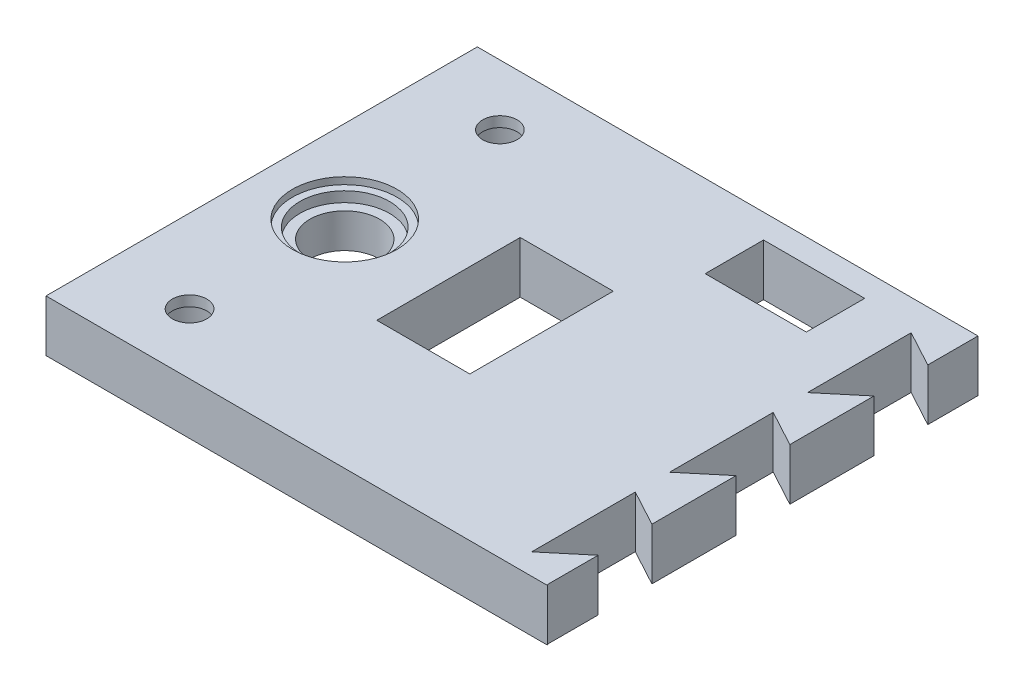
SolidWorks part; units mm, degrees
ref_plane "Front Plane" through (0, 0, 0) normal (0, 0, 1) x (1, 0, 0)
ref_plane "Top Plane" through (0, 0, 0) normal (0, 1, 0) x (1, 0, 0)
ref_plane "Right Plane" through (0, 0, 0) normal (1, 0, 0) x (0, 0, -1)
sketch "Sketch1" plane through (0, 0, 0) normal (0, 1, 0) x (1, 0, 0)
  line L1 (-140, 105) -> (140, 105)
  line L2 (-140, 105) -> (-140, -105)
  line L3 (-140, -105) -> (140, -105)
  line L4 (140, 105) -> (140, -105)
  line L5 (-140, 105) -> (140, -105) construction
  line L6 (-140, -105) -> (140, 105) construction
  point P0 (0, 0)
  dimension "D1" = 280
  dimension "D2" = 210
extrude "Boss-Extrude1" add sketch "Sketch1" along normal blind 15
sketch "Sketch2" plane through (0, 15, 0) normal (0, 1, 0) x (1, 0, 0)
  line L0 (-105, 0) -> (-100, 0) construction
  line L2 (-100, 0) -> (-95, 0) construction
  line L3 (-100, 0) -> (-100, 5) construction
  line L4 (-100, 0) -> (-100, -5) construction
  line L5 (-75, 0) -> (-62.5, 0) construction
  line L6 (-100, -40) -> (-100, -45) construction
  line L7 (-100, 40) -> (-100, 45) construction
  circle A3 centre (-100, 0) radius 5
  circle A4 centre (-100, 45) radius 5
  circle A5 centre (-100, -45) radius 5
  dimension "D3" = 45
  dimension "D4" = 45
  dimension "D2" = 37.5
extrude "Boss-Extrude2" add sketch "Sketch2" along normal blind 50
sketch "Sketch3" plane through (0, 15, 0) normal (0, 1, 0) x (1, 0, 0)
  line L1 (5, 15) -> (-5, 15)
  line L2 (5, 15) -> (5, -15)
  line L3 (5, -15) -> (-5, -15)
  line L4 (-5, 15) -> (-5, -15)
  line L5 (5, 15) -> (-5, -15) construction
  line L6 (5, -15) -> (-5, 15) construction
  point P0 (0, 0)
extrude "Boss-Extrude3" add sketch "Sketch3" along normal up to surface (50 mm away) up to face at (-100, 65, 50)
sketch "Sketch4" plane through (5, 0, 0) normal (1, 0, 0) x (0, 0, -1)
  circle A0 centre (0, 41.2362) radius 13
extrude "Cut-Extrude1" cut sketch "Sketch4" against normal blind 20 contours A0
sketch "Sketch5" plane through (0, 0, 0) normal (0, 1, 0) x (1, 0, 0)
  line L1 (124.0869, 62.5479) -> (-124.0869, 62.5479)
  line L2 (124.0869, 62.5479) -> (124.0869, -62.5479)
  line L3 (124.0869, -62.5479) -> (-124.0869, -62.5479)
  line L4 (-124.0869, 62.5479) -> (-124.0869, -62.5479)
  line L7 (-178.9003, 121.3967) -> (181.5906, 121.3967)
  line L8 (-178.9003, 121.3967) -> (-178.9003, -127.786)
  line L9 (-178.9003, -127.786) -> (181.5906, -127.786)
  line L10 (181.5906, 121.3967) -> (181.5906, -127.786)
  line L11 (-124.0869, 62.5479) -> (124.0869, 62.5479)
  line L13 (-124.0869, 121.3967) -> (181.5906, 121.3967)
  line L14 (181.5906, 62.5479) -> (181.5906, 121.3967)
  line L17 (-124.0869, 121.3967) -> (-178.9003, 121.3967)
  line L18 (-178.9003, 62.5479) -> (-178.9003, 121.3967)
  line L20 (-178.9003, 62.5479) -> (-178.9003, -127.786)
  line L21 (-178.9003, -127.786) -> (-124.0869, -127.786)
  line L22 (-124.0869, 62.5479) -> (-124.0869, -62.5479)
  line L23 (-124.0869, -62.5479) -> (124.0869, -62.5479)
  line L25 (-124.0869, -127.786) -> (181.5906, -127.786)
  line L26 (181.5906, -62.5479) -> (181.5906, -127.786)
  line L28 (124.0869, 62.5479) -> (124.0869, -62.5479)
  line L30 (181.5906, 62.5479) -> (181.5906, -62.5479)
  point P0 (0, 0)
sketch "Sketch6" plane through (0, 0, 0) normal (0, 1, 0) x (1, 0, 0)
extrude "Cut-Extrude5" cut sketch "Sketch5" along normal up to surface (15 mm away) contours L10 L7 L8 L9 L4 L1 L2 L3 up to face at (-100, 15, 50)
sketch "Sketch7" plane through (0, 65, 0) normal (0, 1, 0) x (1, 0, 0)
  circle A0 centre (-100, 45) radius 5
  circle A1 centre (-100, 0) radius 5
  circle A2 centre (-100, -45) radius 5
extrude "Cut-Extrude6" cut sketch "Sketch7" against normal up to surface (65 mm away) up to face at (0, 0, 0)
sketch "Sketch8" plane through (0, 0, 0) normal (0, -1, 0) x (1, 0, 0)
  circle A0 centre (-100, 45) radius 10.1
  circle A1 centre (-100, 0) radius 10.1
  circle A2 centre (-100, -45) radius 10.1
  dimension "D1" = 20.2
  dimension "D2" = 20.2
  dimension "D3" = 20.2
sketch "Sketch9" plane through (0, 15, 0) normal (0, 1, 0) x (1, 0, 0)
  line L0 (-4.7569, 55.5479) -> (-34.0869, 55.5479)
  line L1 (-4.7569, 55.5479) -> (-4.7569, 38.6279)
  line L2 (-4.7569, 38.6279) -> (-34.0869, 38.6279)
  line L3 (-34.0869, 55.5479) -> (-34.0869, 38.6279)
  line L4 (-4.7569, 55.5479) -> (-34.0869, 38.6279) construction
  line L5 (-4.7569, 38.6279) -> (-34.0869, 55.5479) construction
  line L6 (-19.4219, 55.5479) -> (-19.4219, 62.5479) construction
  line L7 (124.0869, 62.5479) -> (-124.0869, 62.5479) construction
  line L8 (-124.0869, 62.5479) -> (-124.0869, -62.5479) construction
  point P0 (-19.4219, 47.0879)
  dimension "D1" = 7
  dimension "D2" = 16.92
  dimension "D3" = 29.33
  dimension "D4" = 90
sketch "Sketch10" plane through (0, 15, 0) normal (0, 1, 0) x (1, 0, 0)
  line L0 (10.618, 13.6516) -> (10.618, -16.4077)
  line L5 (10.618, -56.4077) -> (21.1123, -47.6292)
  line L7 (21.1123, 62.3479) -> (21.1123, 47.9763)
  line L9 (10.618, 53.6516) -> (10.618, 23.5923)
  line L10 (21.1123, -32.0237) -> (10.618, -26.3484)
  line L11 (21.1123, 7.9763) -> (10.618, 13.6516)
  line L12 (10.618, -16.4077) -> (21.1123, -7.6292)
  line L13 (21.1123, 47.9763) -> (10.618, 53.6516)
  line L14 (10.618, 23.5923) -> (21.1123, 32.3708)
  line L15 (10.618, -26.3484) -> (10.618, -56.4077)
  line L20 (21.1123, 32.3708) -> (21.1123, 7.9763)
  line L21 (21.1123, 167.9763) -> (10.618, 173.6516) [skipped]
  line L22 (10.618, 143.5923) -> (21.1123, 152.3708) [skipped]
  line L23 (21.1123, 127.9763) -> (10.618, 133.6516) [skipped]
  line L24 (10.618, 103.5923) -> (21.1123, 112.3708) [skipped]
  line L25 (21.1123, 87.9763) -> (10.618, 93.6516) [skipped]
  line L26 (10.618, 63.5923) -> (21.1123, 72.3708) [skipped]
  line L27 (21.1123, -7.6292) -> (21.1123, -32.0237)
  line L30 (21.1123, -47.6292) -> (21.1123, -62.3479)
  line L32 (115.0289, 75.5324) -> (147.5773, 65.1181)
  line L33 (147.5773, 65.1181) -> (147.5773, -51.5861)
  line L34 (147.5773, -51.5861) -> (118.8593, -85.1466)
  line L35 (118.8593, -85.1466) -> (41.182, -80.6135)
  line L36 (41.182, -80.6135) -> (21.1123, -62.3479)
  line L38 (21.1123, 62.3479) -> (21.1123, 80.7633)
  line L39 (21.1123, 80.7633) -> (115.0289, 75.5324)
  point P16 (0, 0)
  dimension "D2" = 24.3945
  dimension "D3" = 14.3716
  dimension "D4" = 14.7186
  dimension "D1" = 6
sketch "Sketch11" plane through (0, 65, 0) normal (0, 1, 0) x (1, 0, 0)
  line L1 (5.6129, 18.8038) -> (-11.6186, 18.8038)
  line L2 (5.6129, 18.8038) -> (5.6129, -18.5312)
  line L3 (5.6129, -18.5312) -> (-11.6186, -18.5312)
  line L4 (-11.6186, 18.8038) -> (-11.6186, -18.5312)
extrude "Cut-Extrude11" cut sketch "Sketch8" against normal blind 12
sketch "Sketch13" plane through (0, 15, 0) normal (0, 1, 0) x (1, 0, 0)
  line L9 (-43.0154, -20.6978) -> (-70, -20.6978)
  line L10 (-70, 20.8978) -> (-70, -20.6978)
  line L11 (-70, 20.8978) -> (-43.0154, 20.8978)
  line L12 (-43.0154, 20.8978) -> (-43.0154, -20.6978)
  point P0 (-70, 0.1)
  point P2 (-70, 0.1)
  point P4 (-56.6702, 0)
  dimension "D1" = 26.9846
  dimension "D2" = 41.5955
extrude "Cut-Extrude12" cut sketch "Sketch13" against normal through all
extrude "Cut-Extrude13" cut sketch "Sketch11" against normal up to surface (50 mm away) up to face at (-56.5077, 15, -0.1)
extrude "Cut-Extrude16" cut sketch "Sketch10" against normal through all
sketch "Sketch16" plane through (0, 15, 0) normal (0, 1, 0) x (1, 0, 0)
  circle A0 centre (-100, 0) radius 13
  dimension "D1" = 26
extrude "Cut-Extrude20" cut sketch "Sketch16" against normal blind 5
sketch "Sketch17" plane through (0, 0, 0) normal (0, -1, 0) x (1, 0, 0)
  line L0 (-99.5654, 10.0642) -> (-99.5454, 10.0642)
  line L2 (-99.1501, 10.0642) -> (-99.1501, 12.0642)
  line L3 (-99.1501, 12.0642) -> (-100.6501, 12.0642)
  line L4 (-100.6501, 10.0642) -> (-100.6501, 12.0642)
  line L5 (-99.5454, 10.0642) -> (-100.6501, 12.0642) construction
  line L6 (-99.1501, 12.0642) -> (-99.5654, 10.0642) construction
  line L7 (-100.6501, 10.0642) -> (-100.7264, 9.2132)
  line L8 (-100.7264, 9.2132) -> (-99.1501, 9.4228)
  line L9 (-99.1501, 9.4228) -> (-99.1501, 10.0642)
  circle A0 centre (-100, 0) radius 10.1 construction
  point P0 (-99.5599, 10.0904)
  dimension "D1" = 1.5
  dimension "D2" = 2
extrude "Cut-Extrude22" cut sketch "Sketch17" against normal blind 2
sketch "Sketch18" plane through (0, 15, 0) normal (0, 1, 0) x (1, 0, 0)
  circle A0 centre (-100, 0) radius 15.15
  dimension "D1" = 30.3
extrude "Cut-Extrude23" cut sketch "Sketch18" against normal blind 2
extrude "Cut-Extrude24" cut sketch "Sketch9" against normal through all
